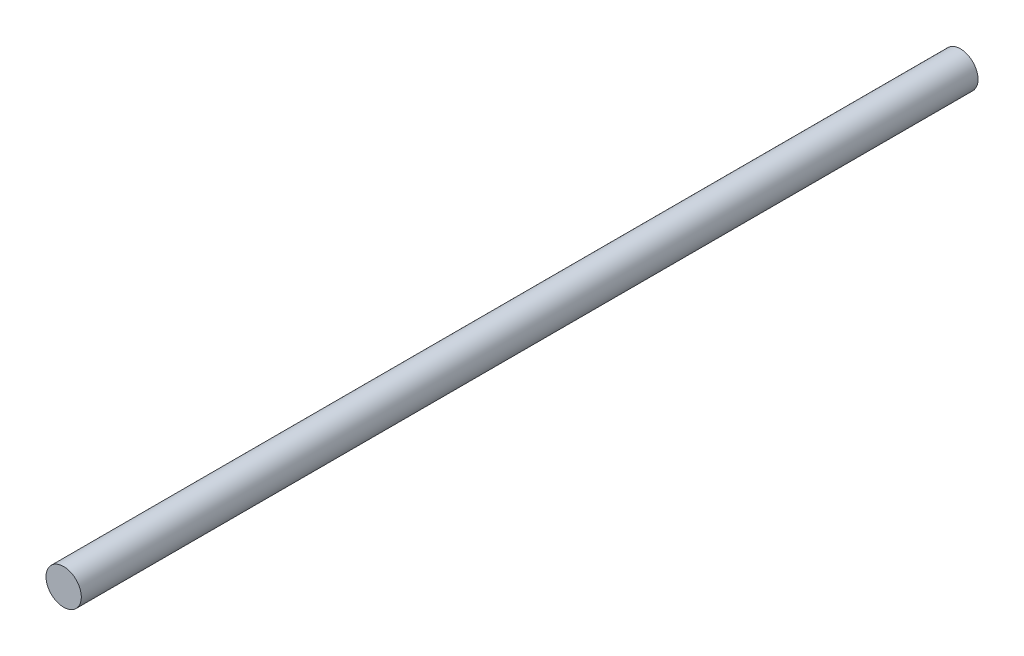
SolidWorks part; units mm, degrees
ref_plane "Front Plane" through (0, 0, 0) normal (0, 0, 1) x (1, 0, 0)
ref_plane "Top Plane" through (0, 0, 0) normal (0, 1, 0) x (1, 0, 0)
ref_plane "Right Plane" through (0, 0, 0) normal (1, 0, 0) x (0, 0, -1)
sketch "Sketch1" plane through (0, 0, 0) normal (0, 0, 1) x (1, 0, 0)
  circle A0 centre (0, 0) radius 6
  dimension "D1" = 12
extrude "Boss-Extrude1" add sketch "Sketch1" along normal blind 304.8
